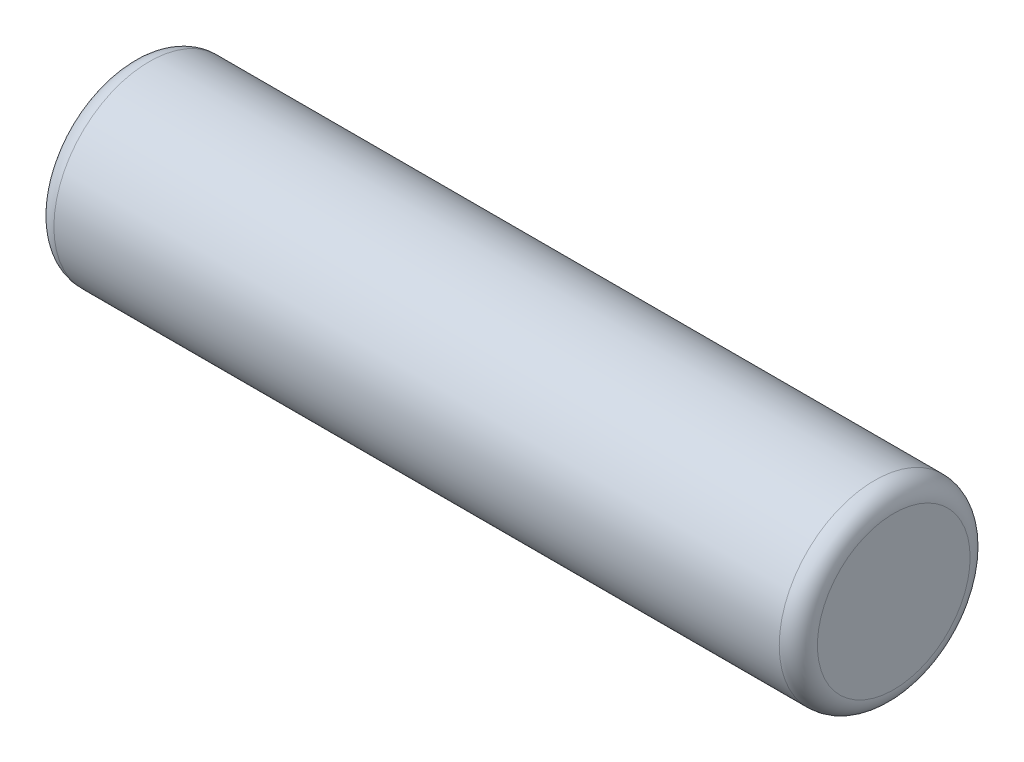
SolidWorks part; units mm, degrees
ref_plane "Front Plane" through (0, 0, 0) normal (0, 0, 1) x (1, 0, 0)
ref_plane "Top Plane" through (0, 0, 0) normal (0, 1, 0) x (1, 0, 0)
ref_plane "Right Plane" through (0, 0, 0) normal (1, 0, 0) x (0, 0, -1)
sketch "Sketch1" plane through (0, 0, 0) normal (1, 0, 0) x (0, 0, -1)
  circle A0 centre (0, 0) radius 12.7
  dimension "D1" = 25.4
extrude "Boss-Extrude1" add sketch "Sketch1" against normal blind 101.6
fillet "Fillet1" radius 2.54 2 edges at (-101.6, 0, -12.7) (0, 0, -12.7)
